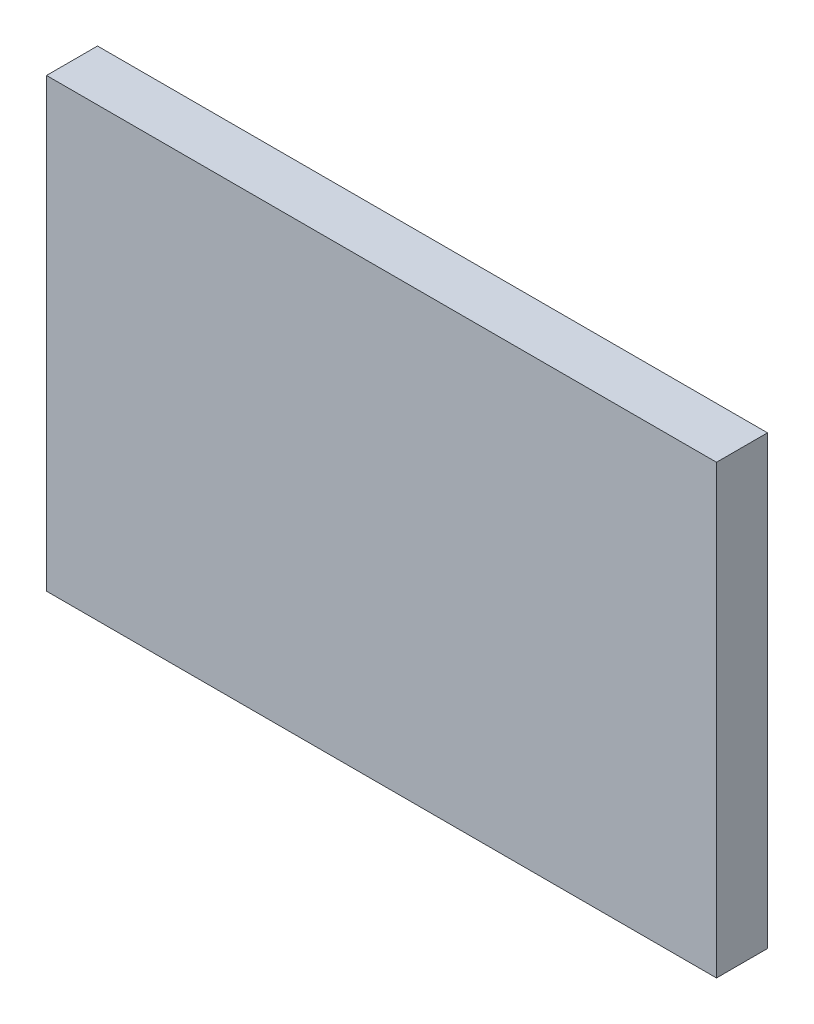
SolidWorks part; units mm, degrees
ref_plane "Alzado" through (0, 0, 0) normal (0, 0, 1) x (1, 0, 0)
ref_plane "Planta" through (0, 0, 0) normal (0, 1, 0) x (1, 0, 0)
ref_plane "Vista lateral" through (0, 0, 0) normal (1, 0, 0) x (0, 0, -1)
sketch "Croquis1" plane through (0, 0, 0) normal (0, 0, 1) x (1, 0, 0)
  line L1 (0, 0) -> (38.1, 0)
  line L2 (0, 0) -> (0, -25.4)
  line L3 (0, -25.4) -> (38.1, -25.4)
  line L4 (38.1, 0) -> (38.1, -25.4)
  dimension "D1" = 25.4
  dimension "D2" = 38.1
extrude "Saliente-Extruir1" add sketch "Croquis1" along normal blind 2.9
